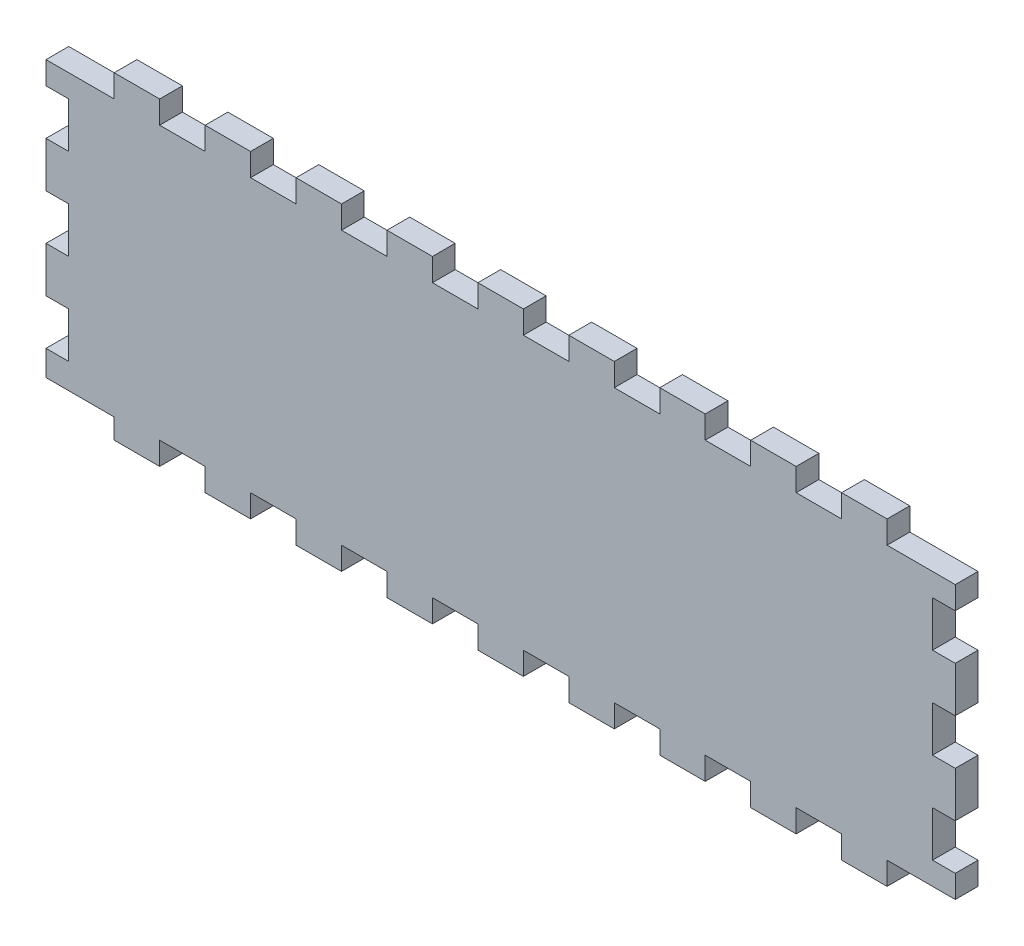
SolidWorks part; units mm, degrees
ref_plane "Front Plane" through (0, 0, 0) normal (1, 0, 0) x (0, 1, 0)
ref_plane "Top Plane" through (0, 0, 0) normal (0, 0, 1) x (0, 1, 0)
ref_plane "Right Plane" through (0, 0, 0) normal (0, 1, 0) x (-1, 0, 0)
sketch "Sketch2" plane through (0, 0, 0) normal (1, 0, 0) x (0, 1, 0)
  line L1 (0, 0) -> (88.9, 0)
  line L2 (0, 0) -> (0, 6.35)
  line L3 (0, 6.35) -> (88.9, 6.35)
  line L4 (88.9, 0) -> (88.9, 6.35)
  dimension "D1" = 88.9
  dimension "D2" = 6.35
extrude "Boss-Extrude1" add sketch "Sketch2" along normal blind 254
sketch "Sketch3" plane through (0, 0, 6.35) normal (0, 0, 1) x (1, 0, 0)
  line L0 (0, 88.9) -> (0, 0) construction
  line L1 (0, 12.7) -> (6.35, 12.7)
  line L2 (0, 12.7) -> (0, 25.4)
  line L3 (0, 25.4) -> (6.35, 25.4)
  line L4 (6.35, 12.7) -> (6.35, 25.4)
  line L5 (254, 0) -> (0, 0) construction
  line L6 (247.65, 12.7) -> (254, 12.7)
  line L7 (0, 38.1) -> (6.35, 38.1)
  line L8 (0, 38.1) -> (0, 50.8)
  line L9 (0, 50.8) -> (6.35, 50.8)
  line L10 (6.35, 38.1) -> (6.35, 50.8)
  line L11 (0, 63.5) -> (6.35, 63.5)
  line L12 (0, 63.5) -> (0, 76.2)
  line L13 (0, 76.2) -> (6.35, 76.2)
  line L14 (6.35, 63.5) -> (6.35, 76.2)
  line L15 (247.65, 12.7) -> (247.65, 25.4)
  line L16 (247.65, 25.4) -> (254, 25.4)
  line L17 (254, 12.7) -> (254, 25.4)
  line L18 (247.65, 38.1) -> (254, 38.1)
  line L19 (247.65, 38.1) -> (247.65, 50.8)
  line L20 (247.65, 50.8) -> (254, 50.8)
  line L21 (254, 38.1) -> (254, 50.8)
  line L22 (247.65, 63.5) -> (254, 63.5)
  line L23 (247.65, 63.5) -> (247.65, 76.2)
  line L24 (247.65, 76.2) -> (254, 76.2)
  line L25 (254, 63.5) -> (254, 76.2)
  line L26 (82.55, 0) -> (95.25, 0)
  line L27 (57.15, 0) -> (69.85, 0)
  line L32 (57.15, 0) -> (57.15, 6.35)
  line L33 (57.15, 6.35) -> (69.85, 6.35)
  line L34 (69.85, 0) -> (69.85, 6.35)
  line L35 (82.55, 0) -> (82.55, 6.35)
  line L36 (82.55, 6.35) -> (95.25, 6.35)
  line L37 (95.25, 0) -> (95.25, 6.35)
  line L38 (107.95, 0) -> (120.65, 0)
  line L39 (107.95, 0) -> (107.95, 6.35)
  line L40 (107.95, 6.35) -> (120.65, 6.35)
  line L41 (120.65, 0) -> (120.65, 6.35)
  line L42 (133.35, 0) -> (146.05, 0)
  line L43 (133.35, 0) -> (133.35, 6.35)
  line L44 (133.35, 6.35) -> (146.05, 6.35)
  line L45 (146.05, 0) -> (146.05, 6.35)
  line L46 (158.75, 0) -> (171.45, 0)
  line L47 (158.75, 0) -> (158.75, 6.35)
  line L48 (158.75, 6.35) -> (171.45, 6.35)
  line L49 (171.45, 0) -> (171.45, 6.35)
  line L50 (184.15, 0) -> (196.85, 0)
  line L51 (184.15, 0) -> (184.15, 6.35)
  line L52 (184.15, 6.35) -> (196.85, 6.35)
  line L53 (196.85, 0) -> (196.85, 6.35)
  line L54 (209.55, 0) -> (222.25, 0)
  line L55 (209.55, 0) -> (209.55, 6.35)
  line L56 (209.55, 6.35) -> (222.25, 6.35)
  line L57 (222.25, 0) -> (222.25, 6.35)
  line L58 (234.95, 0) -> (254, 0)
  line L59 (234.95, 0) -> (234.95, 6.35)
  line L60 (234.95, 6.35) -> (254, 6.35)
  line L61 (254, 0) -> (254, 6.35)
  line L62 (82.55, 82.55) -> (95.25, 82.55)
  line L63 (57.15, 82.55) -> (69.85, 82.55)
  line L68 (57.15, 82.55) -> (57.15, 88.9)
  line L69 (57.15, 88.9) -> (69.85, 88.9)
  line L70 (69.85, 82.55) -> (69.85, 88.9)
  line L71 (82.55, 82.55) -> (82.55, 88.9)
  line L72 (82.55, 88.9) -> (95.25, 88.9)
  line L73 (95.25, 82.55) -> (95.25, 88.9)
  line L74 (107.95, 82.55) -> (120.65, 82.55)
  line L75 (107.95, 82.55) -> (107.95, 88.9)
  line L76 (107.95, 88.9) -> (120.65, 88.9)
  line L77 (120.65, 82.55) -> (120.65, 88.9)
  line L78 (133.35, 82.55) -> (146.05, 82.55)
  line L79 (133.35, 82.55) -> (133.35, 88.9)
  line L80 (133.35, 88.9) -> (146.05, 88.9)
  line L81 (146.05, 82.55) -> (146.05, 88.9)
  line L82 (158.75, 82.55) -> (171.45, 82.55)
  line L83 (158.75, 82.55) -> (158.75, 88.9)
  line L84 (158.75, 88.9) -> (171.45, 88.9)
  line L85 (171.45, 82.55) -> (171.45, 88.9)
  line L86 (184.15, 82.55) -> (196.85, 82.55)
  line L87 (184.15, 82.55) -> (184.15, 88.9)
  line L88 (184.15, 88.9) -> (196.85, 88.9)
  line L89 (196.85, 82.55) -> (196.85, 88.9)
  line L90 (209.55, 82.55) -> (222.25, 82.55)
  line L91 (209.55, 82.55) -> (209.55, 88.9)
  line L92 (209.55, 88.9) -> (222.25, 88.9)
  line L93 (222.25, 82.55) -> (222.25, 88.9)
  line L94 (234.95, 82.55) -> (254, 82.55)
  line L95 (234.95, 82.55) -> (234.95, 88.9)
  line L96 (234.95, 88.9) -> (254, 88.9)
  line L97 (254, 82.55) -> (254, 88.9)
  line L98 (254, 88.9) -> (254, 0) construction
  line L99 (254, 88.9) -> (0, 88.9) construction
  line L104 (31.75, 82.55) -> (44.45, 82.55)
  line L105 (19.05, 88.9) -> (0, 88.9)
  line L106 (19.05, 88.9) -> (19.05, 82.55)
  line L107 (19.05, 82.55) -> (0, 82.55)
  line L108 (0, 88.9) -> (0, 82.55)
  line L113 (0, 0) -> (19.05, 0)
  line L114 (0, 0) -> (0, 5.6155)
  line L115 (0, 5.6155) -> (19.05, 5.6155)
  line L116 (19.05, 0) -> (19.05, 5.6155)
  line L117 (31.75, 82.55) -> (31.75, 88.9)
  line L118 (31.75, 88.9) -> (44.45, 88.9)
  line L119 (44.45, 82.55) -> (44.45, 88.9)
  line L120 (31.75, 0) -> (44.45, 0)
  line L121 (31.75, 0) -> (31.75, 6.35)
  line L122 (31.75, 6.35) -> (44.45, 6.35)
  line L123 (44.45, 0) -> (44.45, 6.35)
  dimension "D1" = 6.35
  dimension "D3" = 12.7
  dimension "D4" = 12.7
  dimension "D5" = 12.7
  dimension "D6" = 12.7
  dimension "D7" = 12.7
  dimension "D8" = 6.35
  dimension "D9" = 12.7
  dimension "D10" = 12.7
  dimension "D11" = 12.7
  dimension "D12" = 12.7
  dimension "D13" = 12.7
  dimension "D14" = 12.7
  dimension "D15" = 6.35
  dimension "D16" = 6.35
  dimension "D17" = 0
  dimension "D18" = 19.05
  dimension "D19" = 6.35
  dimension "D20" = 12.7
  dimension "D21" = 6.35
  dimension "D22" = 0
  dimension "D23" = 19.05
  dimension "D24" = 12.7
  dimension "D25" = 6.35
  dimension "D26" = 12.7
  dimension "D27" = 0
  dimension "D28" = 12.7
  dimension "D29" = 6.35
  dimension "D30" = 0
  dimension "D31" = 12.7
  dimension "D32" = 12.7
  dimension "D33" = 6.35
  dimension "D34" = 0
  dimension "D35" = 12.7
  dimension "D36" = 12.7
  dimension "D37" = 6.35
  dimension "D38" = 12.7
  dimension "D39" = 0
  dimension "D40" = 12.7
  dimension "D41" = 6.35
  dimension "D42" = 12.7
  dimension "D43" = 0
  dimension "D44" = 12.7
  dimension "D45" = 6.35
  dimension "D46" = 19.05
  dimension "D47" = 6.35
  dimension "D48" = 12.7
  dimension "D49" = 0
  dimension "D50" = 12.7
  dimension "D51" = 0
  dimension "D52" = 0
  dimension "D53" = 0
  dimension "D54" = 12.7
  dimension "D55" = 6.35
  dimension "D56" = 12.7
  dimension "D57" = 12.7
  dimension "D58" = 6.35
  dimension "D59" = 12.7
  dimension "D60" = 12.7
  dimension "D61" = 6.35
  dimension "D62" = 12.7
  dimension "D63" = 12.7
  dimension "D64" = 6.35
  dimension "D65" = 12.7
  dimension "D66" = 12.7
  dimension "D67" = 6.35
  dimension "D68" = 12.7
  dimension "D69" = 12.7
  dimension "D70" = 6.35
  dimension "D71" = 12.7
  dimension "D72" = 12.7
  dimension "D73" = 6.35
  dimension "D74" = 19.05
  dimension "D75" = 6.35
  dimension "D76" = 12.7
  dimension "D77" = 12.7
  dimension "D78" = 6.35
  dimension "D79" = 0
  dimension "D80" = 12.7
  dimension "D81" = 0
  dimension "D82" = 12.7
  dimension "D83" = 6.35
  dimension "D84" = 12.7
  dimension "D85" = 0
extrude "Cut-Extrude1" cut sketch "Sketch3" against normal blind 254
